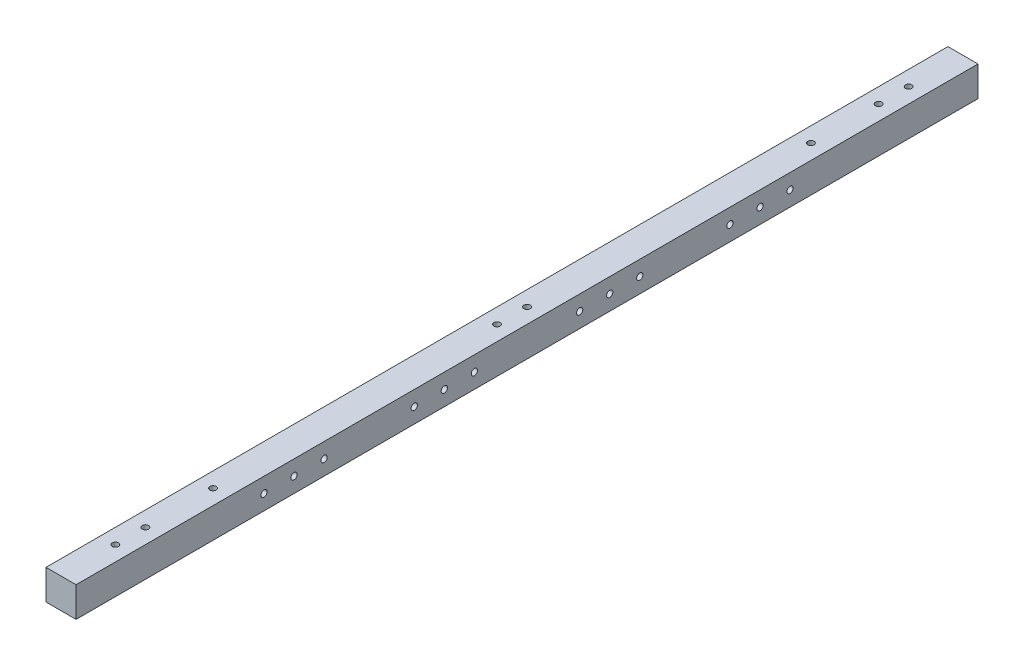
SolidWorks part; units mm, degrees
ref_plane "前视基准面" through (0, 0, 0) normal (0, 0, 1) x (1, 0, 0)
ref_plane "上视基准面" through (0, 0, 0) normal (0, 1, 0) x (1, 0, 0)
ref_plane "右视基准面" through (0, 0, 0) normal (1, 0, 0) x (0, 0, -1)
sketch "草图1" plane through (0, 0, 0) normal (0, 0, 1) x (1, 0, 0)
  line L1 (-10, 10) -> (10, 10)
  line L2 (-10, 10) -> (-10, -10)
  line L3 (-10, -10) -> (10, -10)
  line L4 (10, 10) -> (10, -10)
  line L5 (-10, 10) -> (10, -10) construction
  line L6 (-10, -10) -> (10, 10) construction
  line L11 (-8, 8) -> (8, -8) construction
  line L12 (-8, -8) -> (8, 8) construction
  point P0 (0, 0)
  point P6 (0, 0)
  dimension "D1" = 20
  dimension "D3" = 20
extrude "凸台-拉伸1" add sketch "草图1" along normal blind 600
sketch "草图2" plane through (0, 10, 0) normal (0, 1, 0) x (1, 0, 0)
  line L1 (10, 0) -> (-10, 0) construction
  circle A0 centre (0, -36.12) radius 2.1
  circle A1 centre (0, -56.12) radius 2.1
  circle A2 centre (0, -101.12) radius 2.1
  dimension "D2" = 4.2
  dimension "D3" = 4.2
  dimension "D4" = 20
  dimension "D6" = 45
  dimension "D1" = 36.12
extrude "切除-拉伸1" cut sketch "草图2" against normal blind 30
ref_plane "基准面1" through (0, 0, 300) normal (0, 0, -1) x (-1, 0, 0)
mirror "镜向1" about plane through (0, 0, 300) normal (0, 0, -1) of "切除-拉伸1"
sketch "草图3" plane through (-10, 0, 0) normal (-1, 0, 0) x (0, 0, 1)
  line L0 (300, 10) -> (300, -10) construction
  line L1 (600, 10) -> (0, 10) construction
  line L2 (600, -10) -> (0, -10) construction
  circle A0 centre (225, 0) radius 2.1
  circle A1 centre (245, 0) radius 2.1
  circle A2 centre (265, 0) radius 2.1
  circle A3 centre (375, 0) radius 2.1
  circle A4 centre (355, 0) radius 2.1
  circle A5 centre (335, 0) radius 2.1
  circle A6 centre (435, 0) radius 2.1
  circle A7 centre (455, 0) radius 2.1
  circle A8 centre (475, 0) radius 2.1
  circle A9 centre (125, 0) radius 2.1
  circle A10 centre (145, 0) radius 2.1
  circle A11 centre (165, 0) radius 2.1
  dimension "D1" = 4.2
  dimension "D6" = 60
  dimension "D8" = 4.2
  dimension "D2" = 10
  dimension "D3" = 75
  dimension "D5" = 20
  dimension "D7" = 10
  dimension "D10" = 20
  dimension "D4" = 3
  dimension "D9" = 3
extrude "切除-拉伸2" cut sketch "草图3" against normal through all
sketch "草图4" plane through (0, 10, 0) normal (0, 1, 0) x (1, 0, 0)
  line L0 (-10, -300) -> (10, -300) construction
  line L1 (-10, -600) -> (-10, 0) construction
  line L2 (10, -600) -> (10, 0) construction
  circle A0 centre (0, -310) radius 2.1
  circle A1 centre (0, -290) radius 2.1
  dimension "D1" = 10
  dimension "D2" = 4.2
  dimension "D3" = 10
extrude "切除-拉伸3" cut sketch "草图4" against normal through all
